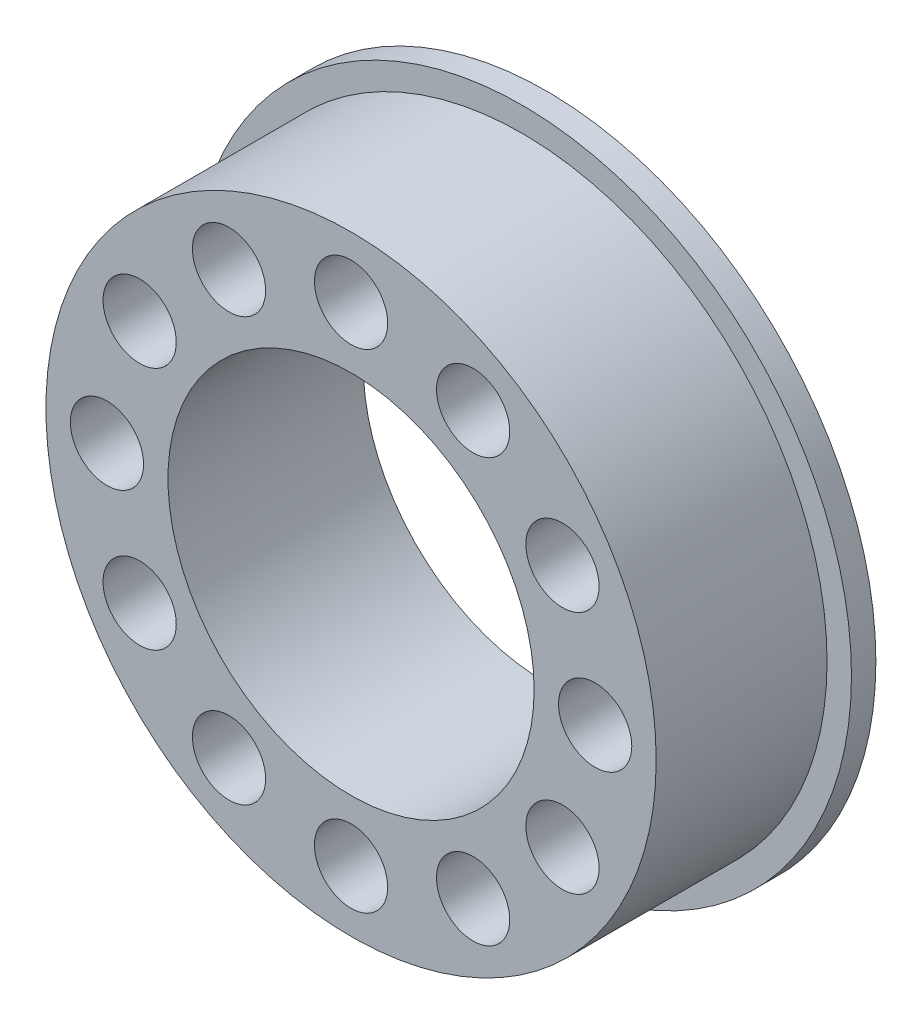
SolidWorks part; units mm, degrees
material "A2017"
ref_plane "正面" through (0, 0, 0) normal (0, 0, 1) x (1, 0, 0)
ref_plane "平面" through (0, 0, 0) normal (0, 1, 0) x (1, 0, 0)
ref_plane "右側面" through (0, 0, 0) normal (1, 0, 0) x (0, 0, -1)
sketch "ｽｹｯﾁ1" plane through (0, 0, 0) normal (1, 0, 0) x (0, 0, -1)
  line L0 (0, 0) -> (14.0759, 0) construction
  line L1 (0, 7.5) -> (8, 7.5)
  line L2 (8, 7.5) -> (8, 13.5)
  line L3 (8, 13.5) -> (7, 13.5)
  line L4 (7, 13.5) -> (7, 12.5)
  line L5 (7, 12.5) -> (0, 12.5)
  line L6 (0, 12.5) -> (0, 7.5)
  point P7 (5.0481, 15.438)
  dimension "D1" = 25
  dimension "D2" = 15
  dimension "D3" = 8
  dimension "D4" = 1
  dimension "D5" = 27
revolve "回転1" add sketch "ｽｹｯﾁ1" angle 360 about L0
sketch "ｽｹｯﾁ2" plane through (0, 0, 0) normal (0, 0, 1) x (1, 0, 0)
  circle A0 centre (0, 0) radius 10 construction
  circle A1 centre (0, 10) radius 1.5
  circle A2 centre (5, 8.6603) radius 1.5
  circle A3 centre (8.6603, 5) radius 1.5
  circle A4 centre (10, 0) radius 1.5
  circle A5 centre (8.6603, -5) radius 1.5
  circle A6 centre (5, -8.6603) radius 1.5
  circle A7 centre (0, -10) radius 1.5
  circle A8 centre (-5, -8.6603) radius 1.5
  circle A9 centre (-8.6603, -5) radius 1.5
  circle A10 centre (-10, 0) radius 1.5
  circle A11 centre (-8.6603, 5) radius 1.5
  circle A12 centre (-5, 8.6603) radius 1.5
  point P5 (0, -10)
  point P29 (0, 0)
  dimension "D1" = 3
  dimension "D2" = 20
  dimension "D3" = 12
extrude "ｶｯﾄ - 押し出し1" cut sketch "ｽｹｯﾁ2" against normal through all
